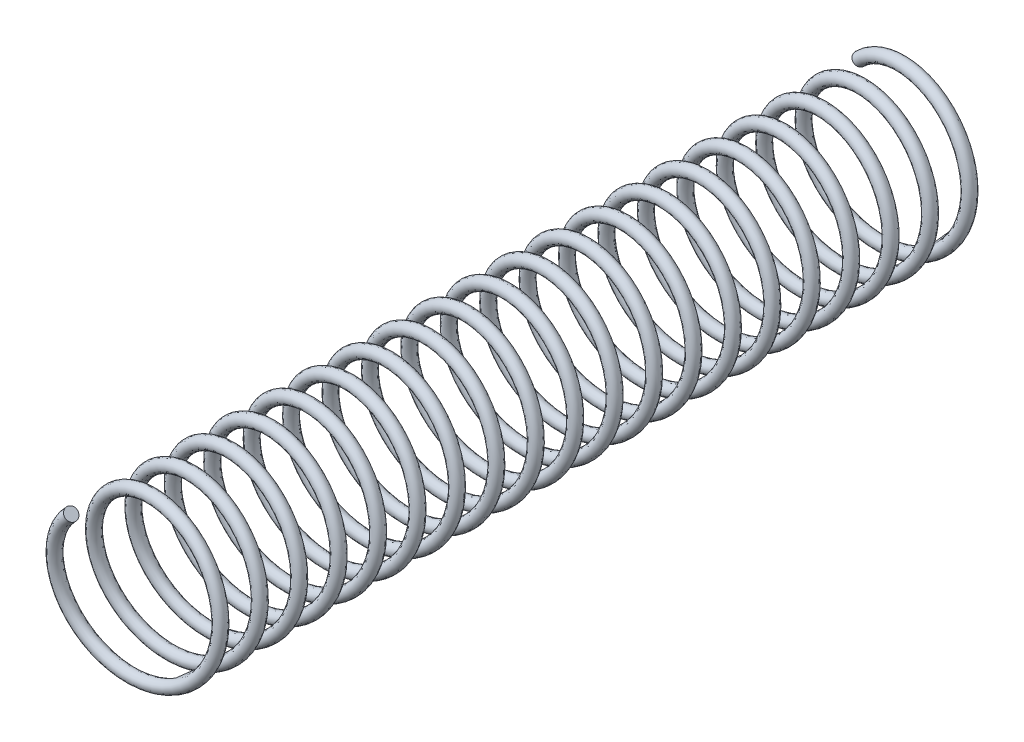
SolidWorks part; units mm, degrees
ref_plane "Front Plane" through (0, 0, 0) normal (0, 0, 1) x (1, 0, 0)
ref_plane "Top Plane" through (0, 0, 0) normal (0, 1, 0) x (1, 0, 0)
ref_plane "Right Plane" through (0, 0, 0) normal (1, 0, 0) x (0, 0, -1)
sketch "Sketch1" plane through (0, 0, 0) normal (0, 0, 1) x (1, 0, 0)
  circle A0 centre (0, 0) radius 7.62
  dimension "D1" = 15.24
curve "Helix/Spiral1" pitch 4.1275 height 82.55 turns 20
ref_plane "Plane1" through (-5.3882, 5.3882, 82.55) normal (0.7045, 0.7045, 0.0859) x (0.0607, 0.0607, -0.9963)
sketch "Sketch2" plane through (-5.3882, 5.3882, 82.55) normal (0.7045, 0.7045, 0.0859) x (0.0607, 0.0607, -0.9963)
  circle A0 centre (0, 0) radius 0.635
  dimension "D1" = 1.27
sweep "Sweep1" add profiles "Sketch2" path "Helix/Spiral1"
